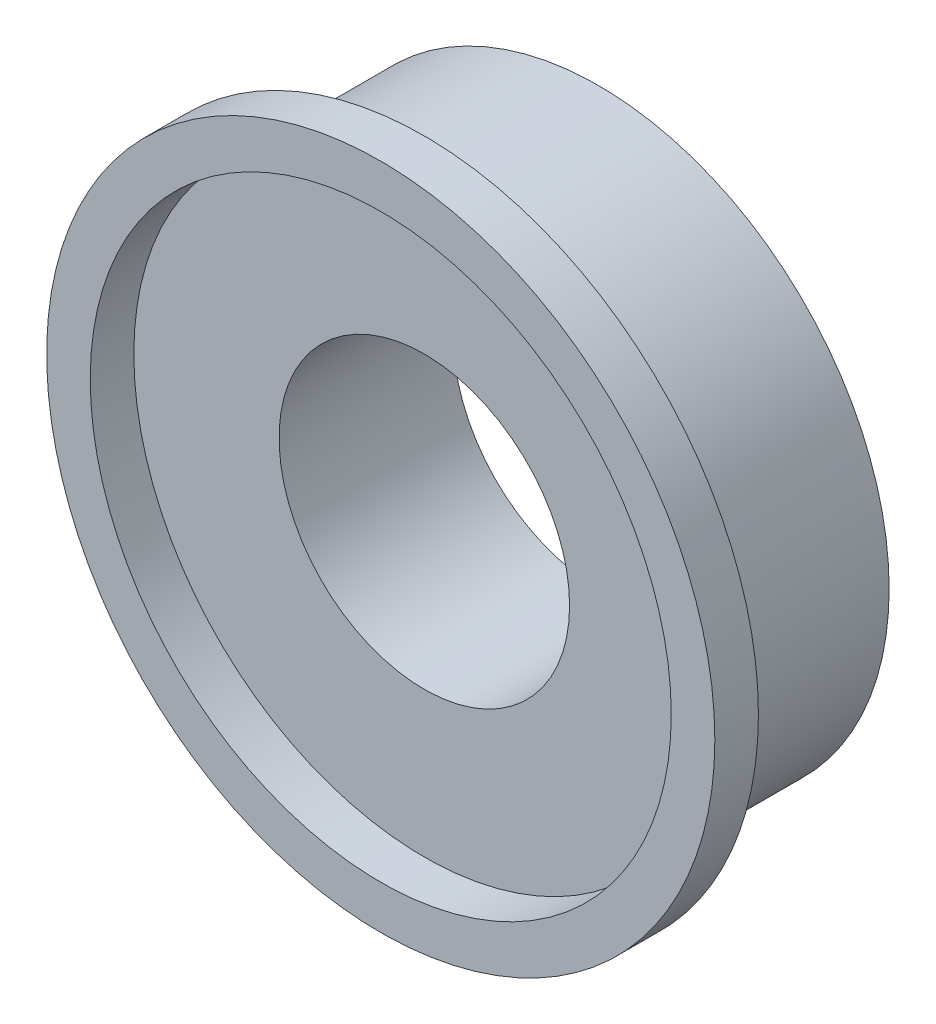
SolidWorks part; units mm, degrees
ref_plane "Ön Düzlem" through (0, 0, 0) normal (0, 0, 1) x (1, 0, 0)
ref_plane "Üst Düzlem" through (0, 0, 0) normal (0, 1, 0) x (1, 0, 0)
ref_plane "Sağ Düzlem" through (0, 0, 0) normal (1, 0, 0) x (0, 0, -1)
sketch "Çizim1" plane through (0, 0, 0) normal (0, 0, 1) x (1, 0, 0)
  circle A0 centre (0, 0) radius 4
  circle A1 centre (0, 0) radius 2
  dimension "D1" = 8
  dimension "D2" = 4
extrude "Yükseklik-Ekstrüzyon1" add sketch "Çizim1" along normal blind 2.4
sketch "Çizim2" plane through (0, 0, 2.4) normal (0, 0, 1) x (1, 0, 0)
  circle A0 centre (0, 0) radius 4.6
  circle A1 centre (0, 0) radius 4
  dimension "D1" = 9.2
extrude "Yükseklik-Ekstrüzyon2" add sketch "Çizim2" along normal blind 0.6 separate body
